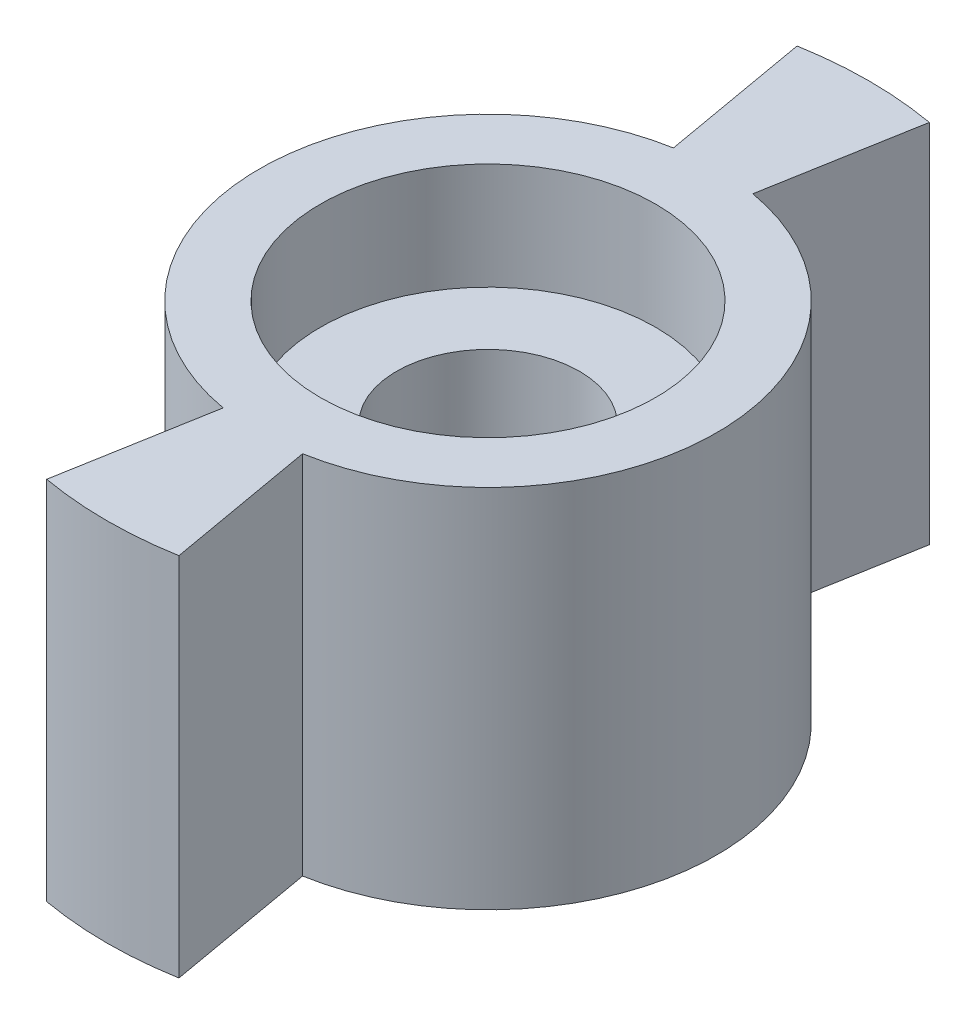
SolidWorks part; units mm, degrees
ref_plane "Front Plane" through (0, 0, 0) normal (0, 0, 1) x (1, 0, 0)
ref_plane "Top Plane" through (0, 0, 0) normal (0, 1, 0) x (1, 0, 0)
ref_plane "Right Plane" through (0, 0, 0) normal (1, 0, 0) x (0, 0, -1)
sketch "Sketch1" plane through (0, 0, 0) normal (0, 0, 1) x (1, 0, 0)
  line L0 (0, 0) -> (0, 24) construction
  line L1 (25, 24) -> (25, 4.5957)
  line L5 (25, 4.5957) -> (25, 0)
  line L6 (25, 0) -> (11, 0)
  line L7 (11, 0) -> (11, 7)
  line L8 (11, 7) -> (6, 7)
  line L9 (6, 7) -> (6, 17)
  line L10 (6, 17) -> (11, 17)
  line L11 (11, 17) -> (11, 24)
  line L12 (11, 24) -> (25, 24)
  point P6 (35, 5.1281)
  dimension "D1" = 24
  dimension "D2" = 25
  dimension "D3" = 7
  dimension "D4" = 7
  dimension "D5" = 11
  dimension "D6" = 11
  dimension "D7" = 6
revolve "Revolve1" add sketch "Sketch1" angle 360 about L0
sketch "Sketch2" plane through (0, 24, 0) normal (0, 1, 0) x (1, 0, 0)
  line L0 (0, 0) -> (4.3412, 24.6202)
  line L1 (0, 0) -> (0, 25) construction
  line L2 (0, 0) -> (-4.3412, 24.6202)
  line L3 (0, 0) -> (24.6202, -4.3412)
  line L4 (0, 0) -> (24.6202, 4.3412)
  line L5 (0, 0) -> (-4.3412, -24.6202)
  line L6 (0, 0) -> (4.3412, -24.6202)
  line L7 (0, 0) -> (-24.6202, 4.3412)
  line L8 (0, 0) -> (-24.6202, -4.3412)
  circle A1 centre (0, 0) radius 25
  circle A2 centre (0, 0) radius 25
  circle A3 centre (0, 0) radius 15
  circle A4 centre (0, 0) radius 25 construction
  point P20 (0, 0)
  circle M7 centre (0, 0) radius 25
  dimension "D5" = 30
  dimension "D2" = 10
  dimension "D3" = 10
  dimension "D1" = 0
  dimension "D4" = 4
extrude "Cut-Extrude2" cut sketch "Sketch2" against normal blind 100 contours A3 L4 L0 M7 | A3 L3 L4 M7 | A3 L6 L3 M7 | A3 L8 L5 M7 | A3 L7 L8 M7 | A3 L2 L7 M7
